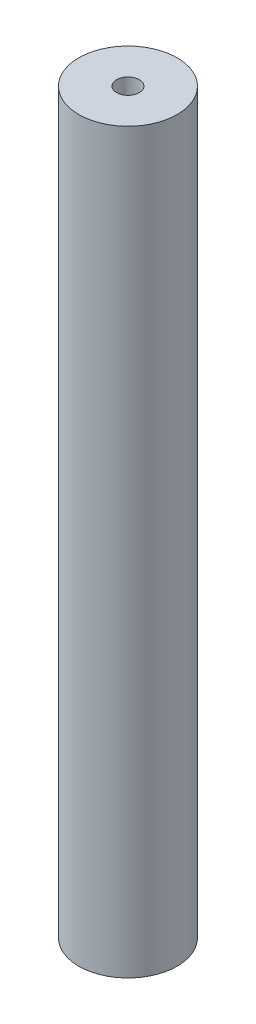
SolidWorks part; units mm, degrees
ref_plane "Front Plane" through (0, 0, 0) normal (0, 0, 1) x (1, 0, 0)
ref_plane "Top Plane" through (0, 0, 0) normal (0, 1, 0) x (1, 0, 0)
ref_plane "Right Plane" through (0, 0, 0) normal (1, 0, 0) x (0, 0, -1)
sketch "Sketch1" plane through (0, 0, 0) normal (0, 1, 0) x (1, 0, 0)
  circle A0 centre (0, 0) radius 5
  circle A1 centre (0, 0) radius 1.15
extrude "Boss-Extrude1" add sketch "Sketch1" along normal blind 75
